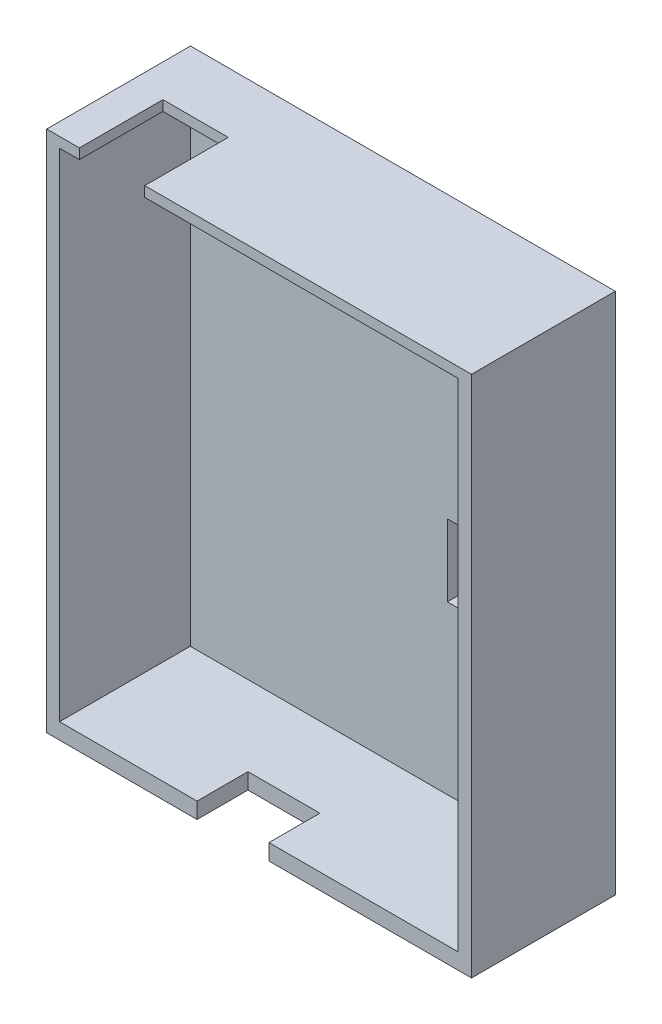
SolidWorks part; units mm, degrees
ref_plane "Piano frontale" through (0, 0, 0) normal (0, 0, 1) x (1, 0, 0)
ref_plane "Piano superiore" through (0, 0, 0) normal (0, 1, 0) x (1, 0, 0)
ref_plane "Piano destro" through (0, 0, 0) normal (1, 0, 0) x (0, 0, -1)
sketch "Schizzo1" plane through (0, 0, 0) normal (0, 0, 1) x (1, 0, 0)
  line L0 (-24.2295, 48.8821) -> (-24.2295, -31.1179)
  line L1 (-24.2295, -31.1179) -> (40.7705, -31.1179)
  line L2 (40.7705, -31.1179) -> (40.7705, 48.8821)
  line L3 (40.7705, 48.8821) -> (-24.2295, 48.8821)
  dimension "D1" = 65
  dimension "D2" = 80
extrude "Estrusione-Estrusione1" add sketch "Schizzo1" along normal blind 22
sketch "Schizzo2" plane through (0, 0, 22) normal (0, 0, 1) x (1, 0, 0)
  line L0 (-22.2648, 47.325) -> (38.7352, 47.325)
  line L1 (38.7352, 47.325) -> (38.7352, -28.675)
  line L2 (38.7352, -28.675) -> (-22.2648, -28.675)
  line L3 (-22.2648, -28.675) -> (-22.2648, 47.325)
  dimension "D1" = 76
  dimension "D2" = 61
extrude "Taglio-Estrusione1" cut sketch "Schizzo2" against normal blind 20
sketch "Schizzo4" plane through (0, -31.1179, 0) normal (0, -1, 0) x (1, 0, 0)
  line L0 (9.7694, 14.2049) -> (-1.2306, 14.2049)
  line L1 (-1.2306, 14.2049) -> (-1.2306, 22.7049)
  line L2 (-1.2306, 22.7049) -> (9.7694, 22.7049)
  line L3 (9.7694, 22.7049) -> (9.7694, 14.2049)
  point P2 (4.2694, 14.2049)
  dimension "D1" = 8.5
  dimension "D2" = 11
extrude "Taglio-Estrusione2" cut sketch "Schizzo4" against normal blind 3
sketch "Schizzo5" plane through (0, 0, 0) normal (0, 0, -1) x (-1, 0, 0)
  line L0 (-40.074, 7.8794) -> (-17.074, 7.8794)
  line L1 (-17.074, 7.8794) -> (-17.074, -3.1206)
  line L2 (-17.074, -3.1206) -> (-40.074, -3.1206)
  line L3 (-40.074, -3.1206) -> (-40.074, 7.8794)
  dimension "D1" = 11
  dimension "D2" = 23
extrude "Taglio-Estrusione3" cut sketch "Schizzo5" against normal blind 3
sketch "Schizzo6" plane through (0, 48.8821, 0) normal (0, 1, 0) x (1, 0, 0)
  line L0 (-19.228, -9.2178) -> (-9.228, -9.2178)
  line L1 (-9.228, -9.2178) -> (-9.228, -23.2178)
  line L2 (-9.228, -23.2178) -> (-19.228, -23.2178)
  line L3 (-19.228, -23.2178) -> (-19.228, -9.2178)
  dimension "D1" = 14
  dimension "D2" = 10
extrude "Taglio-Estrusione4" cut sketch "Schizzo6" against normal blind 3
